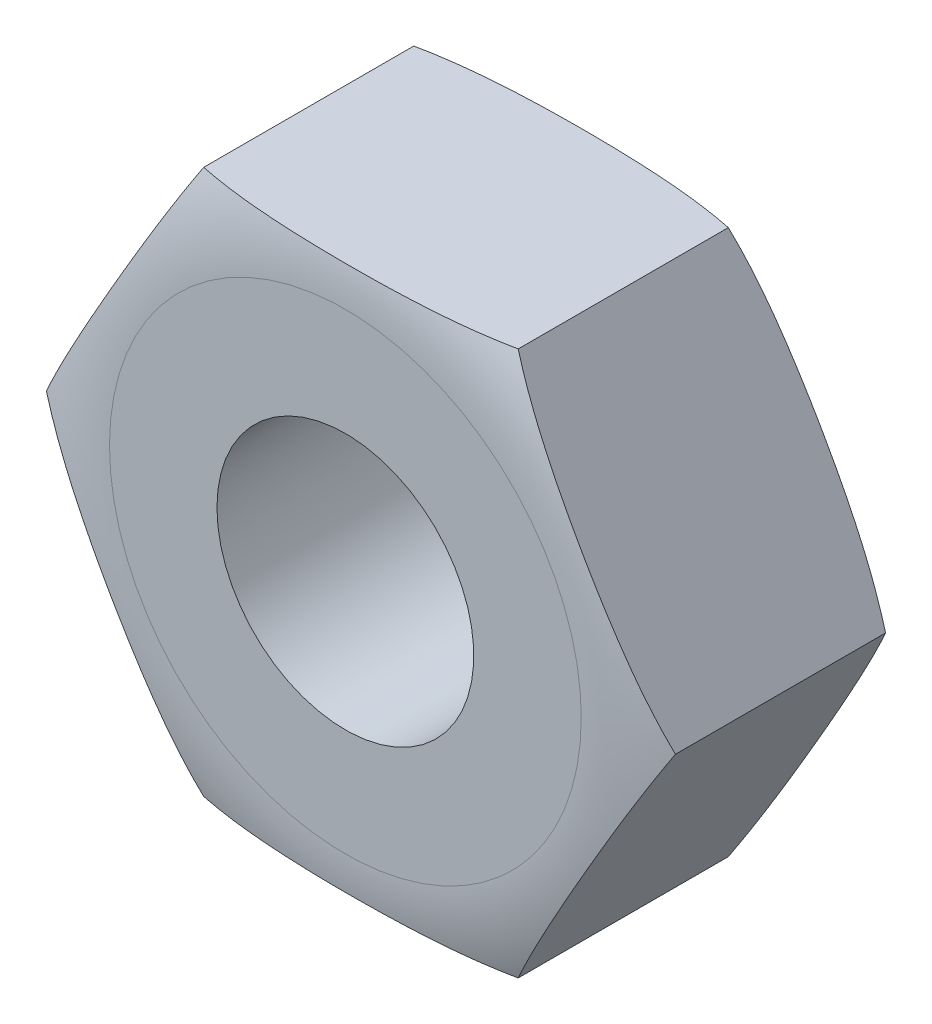
SolidWorks part; units mm, degrees
material "AISI 304"
ref_plane "前视基准面" through (0, 0, 0) normal (0, 0, 1) x (1, 0, 0)
ref_plane "上视基准面" through (0, 0, 0) normal (0, 1, 0) x (1, 0, 0)
ref_plane "右视基准面" through (0, 0, 0) normal (1, 0, 0) x (0, 0, -1)
sketch "草图1" plane through (0, 0, 0) normal (0, 0, 1) x (1, 0, 0)
  line L1 (2.0207, 3.5) -> (-2.0207, 3.5)
  line L2 (-2.0207, 3.5) -> (-4.0415, 0)
  line L3 (-4.0415, 0) -> (-2.0207, -3.5)
  line L4 (-2.0207, -3.5) -> (2.0207, -3.5)
  line L5 (2.0207, -3.5) -> (4.0415, 0)
  line L6 (4.0415, 0) -> (2.0207, 3.5)
  circle A0 centre (0, 0) radius 3.5 construction
  dimension "六角对边" = 7
extrude "螺母的厚度" add sketch "草图1" along normal mid plane 3.1
sketch "草图2" plane through (0, 0, 0) normal (0, 1, 0) x (1, 0, 0)
  line L0 (4.0415, -1.55) -> (4.0415, 1.55) construction
  line L2 (3.0311, 1.55) -> (4.0415, 1.55)
  line L3 (4.0415, 1.55) -> (4.0415, 1.35)
  line L4 (0, 0) -> (0, 0.9918) construction
  line L5 (0, 0) -> (1.8404, 0) construction
  line L6 (4.0415, -1.55) -> (4.0415, -1.35)
  line L7 (3.0311, -1.55) -> (4.0415, -1.55)
  line L8 (4.0415, -1.55) -> (2.0207, -1.55) construction
  arc A0 (4.0415, 1.35) -> (3.0311, 1.55) centre (3.0311, -1.1021) ccw
  arc A1 (4.0415, -1.35) -> (3.0311, -1.55) centre (3.0311, 1.1021) cw
  dimension "D2" = 0.2
revolve "切除-旋转1" cut sketch "草图2" angle 360 about L4
hole_wizard " 螺纹孔1" positions "草图3" profile "草图4" tap size "M1.6" standard "GB" end condition through all
sketch "草图3" plane through (0, 0, -1.55) normal (0, 0, -1) x (-1, 0, 0)
  point P0 (0, 0)
cosmetic thread "孔螺蚊线1" parameters "D2"=5
sketch "草图4" plane through (0, 0, -1.55) normal (1, 0, 0) x (0, 1, 0)
  line L0 (0, 0) -> (0, 3.1)
  line L1 (0, 3.1) -> (1.65, 3.1)
  line L2 (1.65, 3.1) -> (1.65, 0)
  line L5 (1.65, 0) -> (0, 0)
  line L11 (0, -6.35) -> (0, 107.95) construction
  dimension "通孔螺纹孔钻头直径" = 3.3
  dimension "通孔螺纹孔钻头深度" = 3.1
